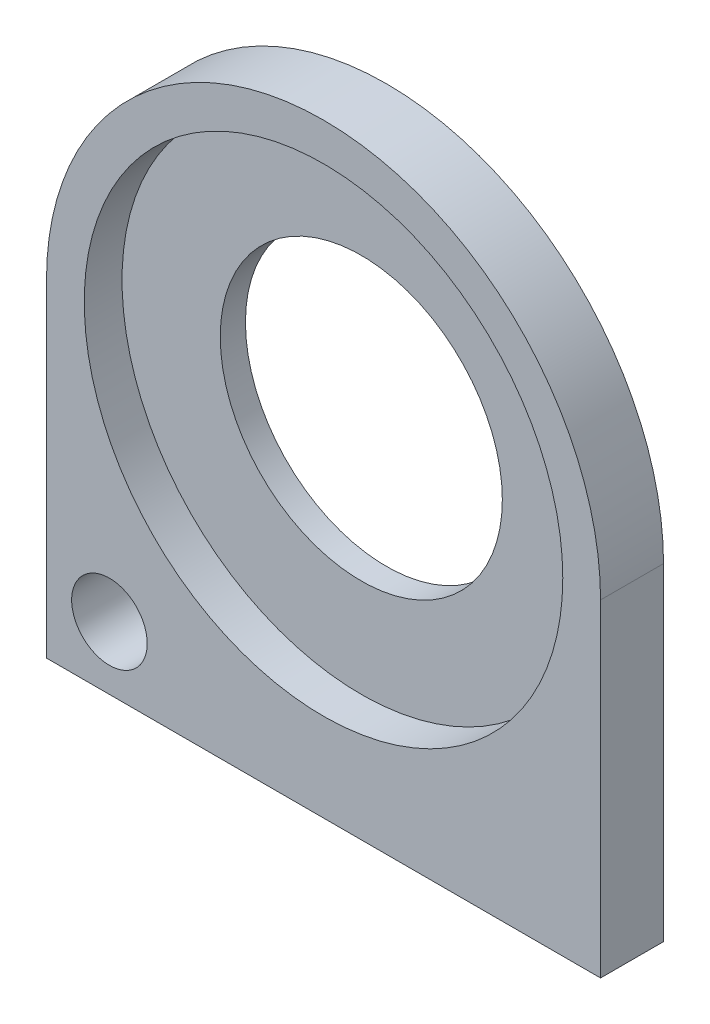
SolidWorks part; units mm, degrees
ref_plane "Plan de face" through (0, 0, 0) normal (0, 0, 1) x (1, 0, 0)
ref_plane "Plan de dessus" through (0, 0, 0) normal (0, 1, 0) x (1, 0, 0)
ref_plane "Plan de droite" through (0, 0, 0) normal (1, 0, 0) x (0, 0, -1)
sketch "Esquisse1" plane through (0, 0, 0) normal (0, 0, 1) x (1, 0, 0)
  line L0 (-22, 9.4518) -> (-22, -3.5482)
  line L1 (-22, -3.5482) -> (0, -3.5482)
  line L2 (0, -3.5482) -> (0, 9.4518)
  arc A0 (-22, 9.4518) -> (0, 9.4518) centre (-11, 9.4518) cw
  circle A1 centre (-11, 9.4518) radius 5.6
  dimension "D1" = 13
extrude "Extrusion1" add sketch "Esquisse1" along normal blind 2.5
sketch "Esquisse2" plane through (0, 0, 2.5) normal (0, 0, 1) x (1, 0, 0)
  circle A0 centre (-11, 9.4518) radius 9.5
extrude "Extrusion2" cut sketch "Esquisse2" against normal blind 1.5
sketch "Esquisse3" plane through (0, 0, 2.5) normal (0, 0, 1) x (1, 0, 0)
  line L0 (-22, 9.4518) -> (-22, -3.5482) construction
  line L1 (-22, -3.5482) -> (0, -3.5482) construction
  circle A0 centre (-19.5, -1.0482) radius 1.5
  dimension "D1" = 2.5
  dimension "D2" = 2.5
extrude "Extrusion3" cut sketch "Esquisse3" against normal through all
